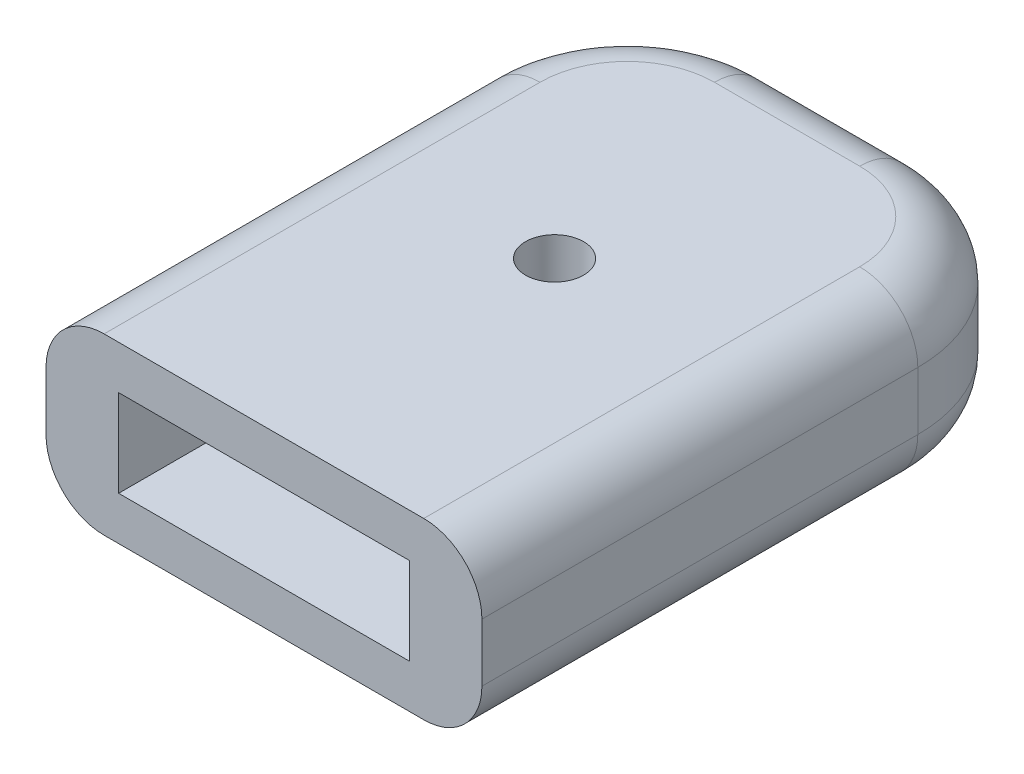
SolidWorks part; units mm, degrees
ref_plane "Front Plane" through (0, 0, 0) normal (0, 0, 1) x (1, 0, 0)
ref_plane "Top Plane" through (0, 0, 0) normal (0, 1, 0) x (1, 0, 0)
ref_plane "Right Plane" through (0, 0, 0) normal (1, 0, 0) x (0, 0, -1)
sketch "Sketch1" plane through (0, 0, 0) normal (0, 1, 0) x (1, 0, 0)
  line L1 (7.5, 10) -> (-7.5, 10)
  line L2 (7.5, 10) -> (7.5, -10)
  line L3 (7.5, -10) -> (-7.5, -10)
  line L4 (-7.5, 10) -> (-7.5, -10)
  line L5 (7.5, 10) -> (-7.5, -10) construction
  line L6 (7.5, -10) -> (-7.5, 10) construction
  point P0 (0, 0)
  dimension "D1" = 15
  dimension "D2" = 20
extrude "Boss-Extrude1" add sketch "Sketch1" along normal blind 6
sketch "Sketch2" plane through (0, 0, 10) normal (0, 0, 1) x (1, 0, 0)
  line L0 (-7.5, 6) -> (-7.5, 0) construction
  line L1 (5, 4.5) -> (-5, 4.5)
  line L2 (5, 4.5) -> (5, 1.5)
  line L3 (5, 1.5) -> (-5, 1.5)
  line L4 (-5, 4.5) -> (-5, 1.5)
  line L5 (5, 4.5) -> (-5, 1.5) construction
  line L6 (5, 1.5) -> (-5, 4.5) construction
  point P0 (0, 3)
  point P5 (0, 0)
  point P7 (0, 0)
  point P10 (-7.5, 3)
  dimension "D1" = 3
  dimension "D2" = 10
extrude "Cut-Extrude1" cut sketch "Sketch2" against normal blind 16
fillet "Fillet1" radius 5 1 edges at (7.5, 3, -10)
fillet "Fillet2" radius 5 1 edges at (-7.5, 3, -10)
fillet "Fillet3" radius 2 10 edges at (7.5, 6, 2.5) (6.0355, 6, -8.5355) (-7.5, 6, 2.5) (-6.0355, 6, -8.5355) (7.5, 0, 2.5) (6.0355, 0, -8.5355) (-7.5, 0, 2.5) (-6.0355, 0, -8.5355) (0, 6, -10) (0, 0, -10)
sketch "Sketch3" plane through (0, 0, 0) normal (0, -1, 0) x (1, 0, 0)
  circle A0 centre (0, 0) radius 1
  dimension "D1" = 2
extrude "Cut-Extrude2" cut sketch "Sketch3" against normal blind 16
